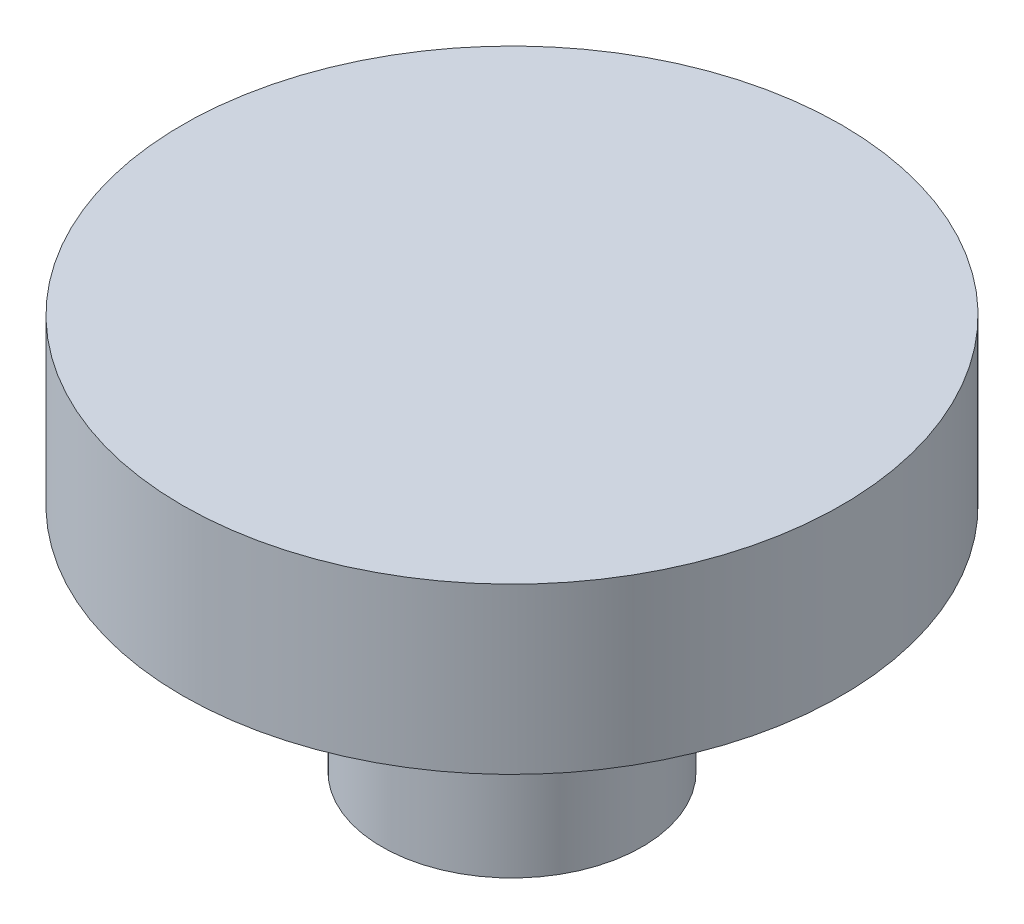
SolidWorks part; units mm, degrees
ref_plane "Front Plane" through (0, 0, 0) normal (0, 0, 1) x (1, 0, 0)
ref_plane "Top Plane" through (0, 0, 0) normal (0, 1, 0) x (1, 0, 0)
ref_plane "Right Plane" through (0, 0, 0) normal (1, 0, 0) x (0, 0, -1)
sketch "Sketch1" plane through (-645.7191, 0, 411.176) normal (0, -1, 0) x (-0.423, 0, 0.9061)
  circle A0 centre (52.9877, -483.5449) radius 10
extrude "Boss-Extrude1" add sketch "Sketch1" along normal blind 5
sketch "Sketch2" plane through (0, -5, 0) normal (0, -1, 0) x (-0.423, 0, 0.9061)
  circle A0 centre (698.7068, -72.369) radius 3.95
extrude "Boss-Extrude2" add sketch "Sketch2" along normal blind 7 contours A0
